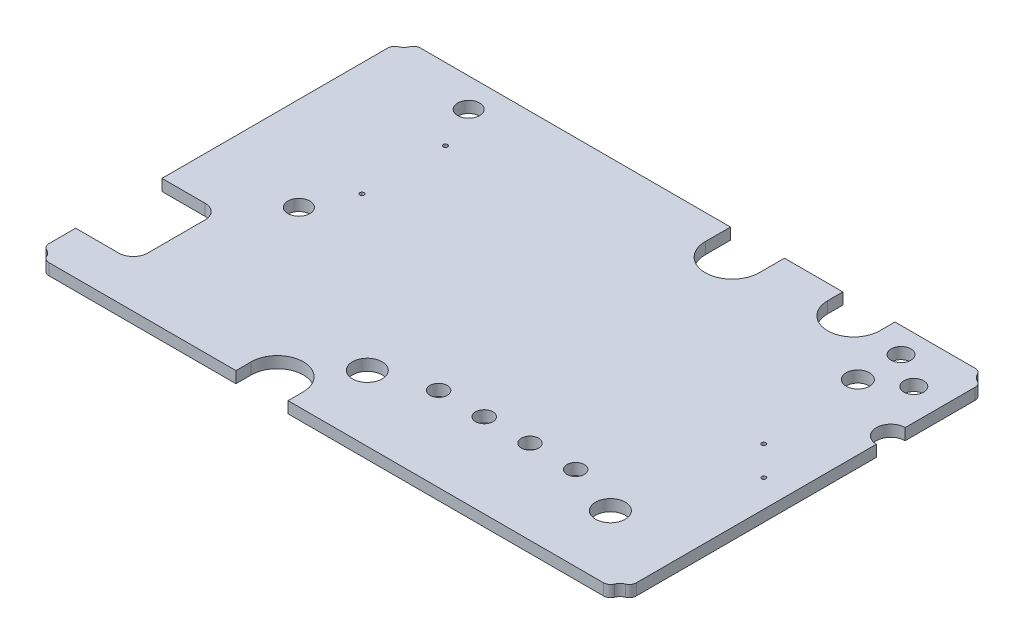
SolidWorks part; units mm, degrees
material "Copper"
ref_plane "Front Plane" through (0, 0, 0) normal (0, 0, 1) x (1, 0, 0)
ref_plane "Top Plane" through (0, 0, 0) normal (0, 1, 0) x (1, 0, 0)
ref_plane "Right Plane" through (0, 0, 0) normal (1, 0, 0) x (0, 0, -1)
sketch "Sketch1" plane through (0, 0, 0) normal (0, 1, 0) x (1, 0, 0)
  line L0 (45, 0) -> (35, 0) construction
  line L1 (-40.825, 25.825) -> (40.825, 25.825) construction
  line L2 (-40.825, 25.825) -> (-40.825, -25.825) construction
  line L3 (-40.825, -25.825) -> (40.825, -25.825) construction
  line L4 (40.825, 25.825) -> (40.825, -25.825) construction
  line L5 (-40.825, 25.825) -> (40.825, -25.825) construction
  line L6 (-40.825, -25.825) -> (40.825, 25.825) construction
  line L7 (45, -30) -> (-45, -30) construction
  line L8 (45, -30) -> (45, 30) construction
  line L9 (45, 30) -> (-45, 30) construction
  line L10 (-45, -30) -> (-45, 30) construction
  line L11 (45, -30) -> (-45, 30) construction
  line L12 (45, 30) -> (-45, -30) construction
  line L13 (35, -30) -> (35, 30) construction
  line L14 (-35, 30) -> (-35, -30) construction
  line L15 (-35, 0) -> (-45, 0) construction
  line L16 (36.25, -30) -> (36.25, 30) construction
  circle A0 centre (-40.825, 25.825) radius 1.5 construction
  circle A1 centre (40.825, 25.825) radius 1.5 construction
  circle A2 centre (40.825, -25.825) radius 1.5 construction
  circle A3 centre (-40.825, -25.825) radius 1.5 construction
  point P0 (0, 0)
  point P12 (0, 0)
  dimension "D3" = 3
  dimension "D1" = 51.65
  dimension "D2" = 81.65
  dimension "D4" = 60
  dimension "D5" = 90
  dimension "D6" = 10
  dimension "D7" = 10
  dimension "D8" = 8.75
sketch "Sketch3" plane through (0, 0, 0) normal (0, 1, 0) x (1, 0, 0)
  line L0 (-38.5337, -25.825) -> (38.5337, -25.825)
  line L1 (-40.825, -25.825) -> (40.825, -25.825) construction
  line L2 (40.825, -23.5337) -> (40.825, 23.5337)
  line L3 (40.825, 25.825) -> (40.825, -25.825) construction
  line L4 (38.5337, 25.825) -> (-38.5337, 25.825)
  line L5 (-40.825, 25.825) -> (40.825, 25.825) construction
  line L6 (-40.825, 23.5337) -> (-40.825, -23.5337)
  line L7 (-40.825, 25.825) -> (-40.825, -25.825) construction
  circle A0 centre (-40.825, -25.825) radius 1.5 construction
  circle A1 centre (40.825, -25.825) radius 1.5 construction
  circle A2 centre (40.825, 25.825) radius 1.5 construction
  circle A3 centre (-40.825, 25.825) radius 1.5 construction
  arc A4 (40.225, 24.4502) -> (39.4502, 25.225) centre (40.825, 25.825) cw
  arc A5 (40.225, -24.4502) -> (39.4502, -25.225) centre (40.825, -25.825) ccw
  arc A6 (-39.4502, -25.225) -> (-40.225, -24.4502) centre (-40.825, -25.825) ccw
  arc A7 (-40.225, 24.4502) -> (-39.4502, 25.225) centre (-40.825, 25.825) ccw
  arc A8 (-38.5337, 25.825) -> (-39.4502, 25.225) centre (-38.5337, 24.825) ccw
  arc A9 (-40.825, 23.5337) -> (-40.225, 24.4502) centre (-39.825, 23.5337) cw
  arc A10 (40.225, 24.4502) -> (40.825, 23.5337) centre (39.825, 23.5337) cw
  arc A11 (40.825, -23.5337) -> (40.225, -24.4502) centre (39.825, -23.5337) cw
  arc A12 (38.5337, -25.825) -> (39.4502, -25.225) centre (38.5337, -24.825) ccw
  arc A13 (-38.5337, -25.825) -> (-39.4502, -25.225) centre (-38.5337, -24.825) cw
  arc A14 (-40.825, -23.5337) -> (-40.225, -24.4502) centre (-39.825, -23.5337) ccw
  arc A15 (39.4502, 25.225) -> (38.5337, 25.825) centre (38.5337, 24.825) ccw
  point P30 (-39.325, 25.825)
  point P33 (-40.825, 24.325)
  point P40 (40.825, 24.325)
  point P43 (40.825, -24.325)
  point P46 (39.325, -25.825)
  point P49 (-39.325, -25.825)
  point P52 (-40.825, -24.325)
  point P55 (39.325, 25.825)
  dimension "D1" = 1
  dimension "D2" = 1
  dimension "D3" = 1
  dimension "D4" = 1
extrude "Boss-Extrude2" add sketch "Sketch3" along normal blind 1.587
sketch "Sketch5" plane through (0, 0, 0) normal (0, 1, 0) x (1, 0, 0)
  line L0 (22.9734, -14.125) -> (16.6234, -14.125) construction
  line L1 (16.6234, -14.125) -> (10.2734, -14.125) construction
  line L2 (10.2734, -14.125) -> (3.9234, -14.125) construction
  line L3 (-3.4466, -16.665) -> (30.3434, -16.665) construction
  line L4 (13.4484, -16.665) -> (13.4484, -14.125) construction
  line L5 (-25.0574, 4.2) -> (-25.0574, 15.8) construction
  line L6 (-27.8254, -1.8) -> (-27.8254, 21.8) construction
  line L7 (-25.0574, 10) -> (-27.8254, 10) construction
  line L8 (40.825, 25.825) -> (40.825, -25.825) construction
  line L9 (-40.825, -25.825) -> (40.825, -25.825) construction
  line L10 (13.4484, -14.125) -> (13.4484, -21.8773) construction
  line L11 (40.825, 25.825) -> (32.475, 25.825) construction
  line L12 (38.5337, 25.825) -> (-38.5337, 25.825) construction
  line L13 (-25.0574, 10) -> (-23.5574, 10) construction
  line L14 (32.475, 25.825) -> (23.475, 25.825) construction
  line L15 (32.475, 25.825) -> (32.475, 11.425) construction
  line L16 (32.475, 11.425) -> (23.475, 11.425) construction
  line L17 (23.475, 25.825) -> (23.475, 11.425) construction
  circle A3 centre (30.3434, -16.665) radius 2.0627
  circle A4 centre (22.9734, -14.125) radius 1.2011
  circle A5 centre (16.6234, -14.125) radius 1.2011
  circle A6 centre (10.2734, -14.125) radius 1.2011
  circle A7 centre (3.9234, -14.125) radius 1.2011
  circle A8 centre (-3.4466, -16.665) radius 2.0627
  circle A9 centre (-27.8254, 21.8) radius 1.525
  circle A10 centre (-27.8254, -1.8) radius 1.525
  circle A11 centre (-25.0574, 15.8) radius 0.3
  circle A12 centre (-25.0574, 4.2) radius 0.3
  dimension "D4" = 0.6
  dimension "D5" = 3.05
  dimension "D1" = 23.6
  dimension "D2" = 11.6
  dimension "D3" = 2.768
  dimension "D6" = 10.4816
  dimension "D7" = 33.79
  dimension "D8" = 9.16
  dimension "D9" = 2.54
  dimension "D10" = 6.35
  dimension "D11" = 8.35
  dimension "D12" = 9
  dimension "D13" = 14.4
  dimension "D14" = 1.5
  dimension "D15" = 23.5574
  dimension "D16" = 10
extrude "Cut-Extrude3" cut sketch "Sketch5" along normal through all
sketch "Sketch6" plane through (0, 1.587, 0) normal (0, 1, 0) x (1, 0, 0)
  line L0 (-27.8254, -1.8) -> (-27.8254, 21.8) construction
  line L1 (-25.0574, 10) -> (-27.8254, 10) construction
  line L2 (-25.0574, 4.2) -> (-25.0574, 15.8) construction
  line L3 (-45, -30) -> (-45, 30) construction
  line L4 (45, -30) -> (-45, -30) construction
  line L5 (45, -30) -> (45, 30) construction
  line L6 (45, 30) -> (-45, 30) construction
  line L7 (40.825, 25.825) -> (40.825, -25.825) construction
  line L8 (-40.825, 25.825) -> (40.825, 25.825) construction
  line L9 (-40.825, -25.825) -> (40.825, -25.825) construction
  line L10 (-40.825, 25.825) -> (-40.825, -25.825) construction
  line L11 (-3.4466, -16.665) -> (30.3434, -16.665) construction
  line L12 (13.4484, -14.125) -> (13.4484, -21.8773) construction
  line L13 (16.6234, -14.125) -> (10.2734, -14.125) construction
  line L14 (22.9734, -14.125) -> (16.6234, -14.125) construction
  line L15 (10.2734, -14.125) -> (3.9234, -14.125) construction
  line L16 (45, 0) -> (35, 0) construction
  line L17 (35, -30) -> (35, 30) construction
  line L18 (-35, 0) -> (-45, 0) construction
  line L19 (-35, 30) -> (-35, -30) construction
  line L20 (-27.8254, -1.8) -> (-27.8254, 21.8) construction
  line L21 (-25.0574, 10) -> (-27.8254, 10) construction
  line L22 (-25.0574, 4.2) -> (-25.0574, 15.8) construction
  line L23 (-45, -30) -> (-45, 30) construction
  line L24 (45, -30) -> (-45, -30) construction
  line L25 (45, -30) -> (45, 30) construction
  line L26 (45, 30) -> (-45, 30) construction
  line L27 (40.825, 25.825) -> (40.825, -25.825) construction
  line L28 (-40.825, 25.825) -> (40.825, 25.825) construction
  line L29 (-40.825, -25.825) -> (40.825, -25.825) construction
  line L30 (-40.825, 25.825) -> (-40.825, -25.825) construction
  line L31 (-3.4466, -16.665) -> (30.3434, -16.665) construction
  line L32 (13.4484, -14.125) -> (13.4484, -21.8773) construction
  line L33 (16.6234, -14.125) -> (10.2734, -14.125) construction
  line L34 (22.9734, -14.125) -> (16.6234, -14.125) construction
  line L35 (10.2734, -14.125) -> (3.9234, -14.125) construction
  line L36 (45, 0) -> (35, 0) construction
  line L37 (35, -30) -> (35, 30) construction
  line L38 (-35, 0) -> (-45, 0) construction
  line L39 (-35, 30) -> (-35, -30) construction
  line L40 (31.75, 22.325) -> (35, 22.325) construction
  line L41 (36.4773, 19.375) -> (35, 19.375) construction
  line L42 (31.75, 16.325) -> (35, 16.325) construction
  circle A0 centre (-27.8254, -1.8) radius 1.525 construction
  circle A1 centre (-25.0574, 4.2) radius 0.3 construction
  circle A2 centre (-25.0574, 15.8) radius 0.3 construction
  circle A3 centre (-27.8254, 21.8) radius 1.525 construction
  circle A4 centre (-40.825, -25.825) radius 1.5 construction
  circle A5 centre (40.825, -25.825) radius 1.5 construction
  circle A6 centre (40.825, 25.825) radius 1.5 construction
  circle A7 centre (-40.825, 25.825) radius 1.5 construction
  circle A8 centre (16.6234, -14.125) radius 1.2011 construction
  circle A9 centre (22.9734, -14.125) radius 1.2011 construction
  circle A10 centre (10.2734, -14.125) radius 1.2011 construction
  circle A11 centre (3.9234, -14.125) radius 1.2011 construction
  circle A12 centre (31.75, 16.325) radius 1.625
  circle A13 centre (31.75, 22.325) radius 1.375
  circle A14 centre (36.4773, 19.375) radius 1.375
  circle A15 centre (-27.8254, -1.8) radius 1.525 construction
  circle A16 centre (-25.0574, 4.2) radius 0.3 construction
  circle A17 centre (-25.0574, 15.8) radius 0.3 construction
  circle A18 centre (-27.8254, 21.8) radius 1.525 construction
  circle A19 centre (-40.825, -25.825) radius 1.5 construction
  circle A20 centre (40.825, -25.825) radius 1.5 construction
  circle A21 centre (40.825, 25.825) radius 1.5 construction
  circle A22 centre (-40.825, 25.825) radius 1.5 construction
  circle A23 centre (16.6234, -14.125) radius 1.2011 construction
  circle A24 centre (22.9734, -14.125) radius 1.2011 construction
  circle A25 centre (10.2734, -14.125) radius 1.2011 construction
  circle A26 centre (3.9234, -14.125) radius 1.2011 construction
  circle A30 centre (35, 0) radius 0.6048 construction
  dimension "D1" = 2.75
  dimension "D2" = 2.75
  dimension "D3" = 3.25
  dimension "D4" = 3.25
  dimension "D5" = 3.25
  dimension "D6" = 1.4773
  dimension "D7" = 3.5
  dimension "D8" = 6.45
  dimension "D9" = 9.5
sketch "Corners" plane through (0, 0, 0) normal (0, -1, 0) x (1, 0, 0)
  line L0 (45, 30) -> (45, -30) construction
  line L1 (45, -30) -> (-45, -30) construction
  line L2 (45, 30) -> (-45, 30) construction
  line L3 (-45, 30) -> (-45, -30) construction
  line L4 (-38.5337, -25.825) -> (38.5337, -25.825)
  line L5 (40.825, -23.5337) -> (40.825, 23.5337)
  line L6 (38.5337, 25.825) -> (-38.5337, 25.825)
  line L7 (-40.825, 23.5337) -> (-40.825, -23.5337)
  line L8 (-38.5337, -25.825) -> (38.5337, -25.825) construction
  line L9 (40.825, -23.5337) -> (40.825, 23.5337) construction
  line L10 (38.5337, 25.825) -> (-38.5337, 25.825) construction
  line L11 (-40.825, 23.5337) -> (-40.825, -23.5337) construction
  line L12 (45, 30) -> (45, -30) construction
  line L13 (45, -30) -> (-45, -30) construction
  line L14 (45, 30) -> (-45, 30) construction
  line L15 (-45, 30) -> (-45, -30) construction
  line L16 (35, 30) -> (35, -30) construction
  line L17 (35, 30) -> (35, -30) construction
  circle A0 centre (-40.825, 25.825) radius 1.5 construction
  circle A1 centre (40.825, 25.825) radius 1.5 construction
  circle A2 centre (40.825, -25.825) radius 1.5 construction
  circle A3 centre (-40.825, -25.825) radius 1.5 construction
  circle A4 centre (-40.825, 25.825) radius 1.5 construction
  circle A5 centre (40.825, 25.825) radius 1.5 construction
  circle A6 centre (40.825, -25.825) radius 1.5 construction
  circle A7 centre (-40.825, -25.825) radius 1.5 construction
  arc A12 (-39.4502, -25.225) -> (-38.5337, -25.825) centre (-38.5337, -24.825) ccw
  arc A13 (38.5337, -25.825) -> (39.4502, -25.225) centre (38.5337, -24.825) ccw
  arc A14 (40.225, -24.4502) -> (39.4502, -25.225) centre (40.825, -25.825) ccw
  arc A15 (40.225, -24.4502) -> (40.825, -23.5337) centre (39.825, -23.5337) ccw
  arc A16 (40.825, 23.5337) -> (40.225, 24.4502) centre (39.825, 23.5337) ccw
  arc A17 (39.4502, 25.225) -> (40.225, 24.4502) centre (40.825, 25.825) ccw
  arc A18 (39.4502, 25.225) -> (38.5337, 25.825) centre (38.5337, 24.825) ccw
  arc A19 (-38.5337, 25.825) -> (-39.4502, 25.225) centre (-38.5337, 24.825) ccw
  arc A20 (-40.225, 24.4502) -> (-39.4502, 25.225) centre (-40.825, 25.825) ccw
  arc A21 (-40.225, 24.4502) -> (-40.825, 23.5337) centre (-39.825, 23.5337) ccw
  arc A22 (-40.825, -23.5337) -> (-40.225, -24.4502) centre (-39.825, -23.5337) ccw
  arc A23 (-39.4502, -25.225) -> (-40.225, -24.4502) centre (-40.825, -25.825) ccw
  arc A24 (-39.4502, -25.225) -> (-38.5337, -25.825) centre (-38.5337, -24.825) ccw construction
  arc A25 (38.5337, -25.825) -> (39.4502, -25.225) centre (38.5337, -24.825) ccw construction
  arc A26 (40.225, -24.4502) -> (39.4502, -25.225) centre (40.825, -25.825) ccw construction
  arc A27 (40.225, -24.4502) -> (40.825, -23.5337) centre (39.825, -23.5337) ccw construction
  arc A28 (40.825, 23.5337) -> (40.225, 24.4502) centre (39.825, 23.5337) ccw construction
  arc A29 (39.4502, 25.225) -> (40.225, 24.4502) centre (40.825, 25.825) ccw construction
  arc A30 (39.4502, 25.225) -> (38.5337, 25.825) centre (38.5337, 24.825) ccw construction
  arc A31 (-38.5337, 25.825) -> (-39.4502, 25.225) centre (-38.5337, 24.825) ccw construction
  arc A32 (-40.225, 24.4502) -> (-39.4502, 25.225) centre (-40.825, 25.825) ccw construction
  arc A33 (-40.225, 24.4502) -> (-40.825, 23.5337) centre (-39.825, 23.5337) ccw construction
  arc A34 (-40.825, -23.5337) -> (-40.225, -24.4502) centre (-39.825, -23.5337) ccw construction
  arc A35 (-39.4502, -25.225) -> (-40.225, -24.4502) centre (-40.825, -25.825) ccw construction
  dimension "D1" = 0
sketch "Sketch8" plane through (0, 1.587, 0) normal (0, 1, 0) x (1, 0, 0)
  line L0 (4.5446, 22.32) -> (4.5446, 25.825)
  line L1 (38.5337, 25.825) -> (-38.5337, 25.825) construction
  line L2 (12.0446, 22.32) -> (12.0446, 25.825)
  circle A0 centre (8.2946, 22.32) radius 1.75 construction
  circle A1 centre (8.2946, 22.32) radius 1.75
  circle A2 centre (8.2946, 22.32) radius 3.75 construction
  arc A3 (4.5446, 22.32) -> (12.0446, 22.32) centre (8.2946, 22.32) ccw
  dimension "D1" = 3.75
extrude "Cut-Extrude4" cut sketch "Sketch8" against normal through all contours L0 A3 L2
sketch "Sketch9" plane through (0, 1.587, 0) normal (0, 1, 0) x (1, 0, 0)
  line L0 (-40.825, 23.5337) -> (-40.825, -23.5337) construction
  line L1 (-40.825, -19.825) -> (-34.825, -19.825)
  line L2 (-40.825, -19.825) -> (-40.825, -7.825)
  line L3 (-40.825, -7.825) -> (-34.825, -7.825)
  line L4 (-32.825, -17.825) -> (-32.825, -9.825)
  line L5 (-38.5337, -25.825) -> (38.5337, -25.825) construction
  arc A0 (-34.825, -19.825) -> (-32.825, -17.825) centre (-34.825, -17.825) ccw
  arc A1 (-32.825, -9.825) -> (-34.825, -7.825) centre (-34.825, -9.825) ccw
  point P10 (-32.825, -19.825)
  point P13 (-32.825, -7.825)
  dimension "D4" = 2
  dimension "D1" = 8
  dimension "D2" = 12
  dimension "D3" = 6
extrude "Cut-Extrude5" cut sketch "Sketch9" against normal through all
sketch "Sketch10" plane through (0, 1.587, 0) normal (0, 1, 0) x (1, 0, 0)
  line L0 (20.665, 23.705) -> (20.665, 26.825) construction
  line L1 (26.905, 23.705) -> (26.905, 26.825) construction
  line L2 (20.665, 23.705) -> (20.665, 26.825) construction
  line L3 (26.905, 23.705) -> (26.905, 26.825) construction
  line L4 (20.165, 23.705) -> (20.165, 26.825)
  line L5 (27.405, 23.705) -> (27.405, 26.825)
  line L7 (27.405, 26.825) -> (20.165, 26.825)
  arc A0 (20.665, 23.705) -> (23.785, 20.585) centre (23.785, 23.705) ccw construction
  arc A1 (23.785, 20.585) -> (26.905, 23.705) centre (23.785, 23.705) ccw construction
  arc A2 (20.665, 23.705) -> (23.785, 20.585) centre (23.785, 23.705) ccw construction
  arc A3 (23.785, 20.585) -> (26.905, 23.705) centre (23.785, 23.705) ccw construction
  arc A4 (20.165, 23.705) -> (23.785, 20.085) centre (23.785, 23.705) ccw
  arc A5 (23.785, 20.085) -> (27.405, 23.705) centre (23.785, 23.705) ccw
  dimension "D1" = 0.5
extrude "Cut-Extrude7" cut sketch "Sketch10" against normal through all
sketch "Sketch12" plane through (0, 1.587, 0) normal (0, 1, 0) x (1, 0, 0)
  line L0 (-12.0439, -23.705) -> (-12.0439, -26.825) construction
  line L1 (-5.8039, -26.825) -> (-5.8039, -23.705) construction
  line L2 (-12.5439, -26.825) -> (-5.3039, -26.825)
  line L3 (-40.825, 25.825) -> (-40.825, -25.825) construction
  line L5 (-5.3039, -23.705) -> (-12.5439, -23.705) construction
  line L9 (-5.3039, -26.825) -> (-5.3039, -23.705)
  line L10 (-12.5439, -23.705) -> (-12.5439, -26.825)
  arc A0 (-12.5439, -23.705) -> (-5.3039, -23.705) centre (-8.9239, -23.705) cw
  arc A1 (-12.0439, -23.705) -> (-5.8039, -23.705) centre (-8.9239, -23.705) cw construction
  dimension "D1" = 31.9011
  dimension "D2" = 7.24
extrude "Cut-Extrude8" cut sketch "Sketch12" against normal through all
sketch "Sketch14" plane through (0, 1.587, 0) normal (0, 1, 0) x (1, 0, 0)
  line L0 (40.825, -23.5337) -> (40.825, 23.5337) construction
  line L1 (38.5337, 25.825) -> (27.405, 25.825) construction
  arc A0 (40.825, 9.825) -> (40.825, 13.825) centre (40.825, 11.825) cw
  dimension "D1" = 2
  dimension "D2" = 14
extrude "Cut-Extrude9" cut sketch "Sketch14" against normal through all and the other way through all flip side to cut
extrude "Cut-Extrude10" cut sketch "Sketch6" against normal through all
sketch "Sketch18" plane through (0, 1.587, 0) normal (0, 1, 0) x (1, 0, 0)
  circle A0 centre (32.968, 2.032) radius 0.2921 construction
  circle A1 centre (32.968, 2.032) radius 0.2921
  circle A2 centre (37.032, -2.032) radius 0.2921 construction
  circle A3 centre (37.032, -2.032) radius 0.2921
extrude "Cut-Extrude11" cut sketch "Sketch18" against normal through all
sketch "Sketch19" plane through (0, 0, 0) normal (0, -1, 0) x (-1, 0, 0)
  point P0 (0, 0)
